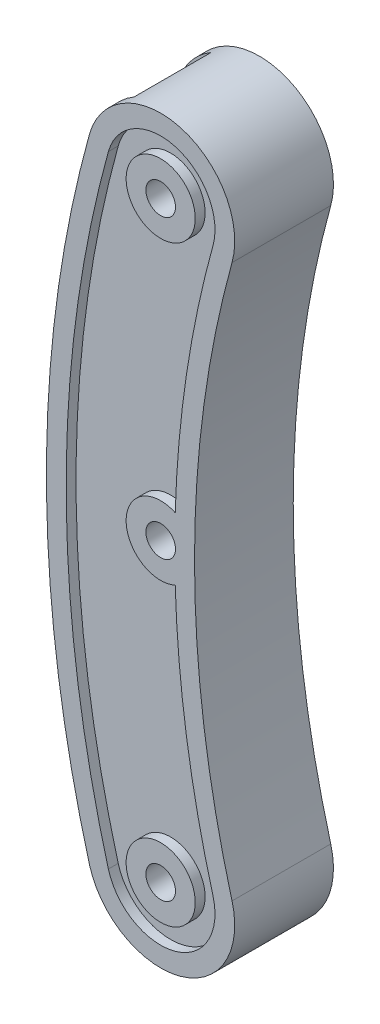
SolidWorks part; units mm, degrees
ref_plane "Front Plane" through (0, 0, 0) normal (0, 0, 1) x (1, 0, 0)
ref_plane "Top Plane" through (0, 0, 0) normal (0, 1, 0) x (1, 0, 0)
ref_plane "Right Plane" through (0, 0, 0) normal (1, 0, 0) x (0, 0, -1)
sketch "Sketch1" plane through (0, 0, 0) normal (0, 0, 1) x (1, 0, 0)
  line L0 (0, 0) -> (-135.8667, 37.5924) construction
  line L2 (-145.3729, 0) -> (0, 0) construction
  line L3 (0, 0) -> (-135.8667, -37.5924) construction
  line L4 (-108.4262, 30) -> (-108.4262, -30) construction
  circle A0 centre (0, 0) radius 105
  circle A1 centre (0, 0) radius 120
  arc A2 (-115.6547, 32) -> (-101.1978, 28) centre (-108.4262, 30) cw
  arc A3 (-115.6547, -32) -> (-101.1978, -28) centre (-108.4262, -30) ccw
  circle A4 centre (-108.4262, -30) radius 1.5
  circle A5 centre (-108.4262, 0) radius 1.5
  circle A6 centre (-108.4262, 30) radius 1.5
  dimension "D1" = 240
  dimension "D2" = 210
  dimension "D4" = 3
  dimension "D3" = 60
extrude "Boss-Extrude1" add sketch "Sketch1" along normal mid plane 10 contours A1 A3 A0 A2 A6 A5 A4
sketch "Sketch2" plane through (0, 0, 5) normal (0, 0, 1) x (1, 0, 0)
  circle A5 centre (-108.4262, -30) radius 3.5
  circle A6 centre (-108.4262, -30) radius 3.5
  arc A10 (-113.7271, 31.4667) -> (-113.7271, -31.4667) centre (0, 0) ccw
  circle A11 centre (-108.4262, 0) radius 3.5
  circle A12 centre (-108.4262, 0) radius 3.5
  circle A14 centre (-108.4262, 30) radius 3.5
  circle A15 centre (-108.4262, 30) radius 3.5
  arc A18 (-113.7271, -31.4667) -> (-103.1254, -28.5333) centre (-108.4262, -30) ccw
  arc A19 (-103.1254, 28.5333) -> (-103.1254, -28.5333) centre (0, 0) ccw
  arc A20 (-103.1254, 28.5333) -> (-113.7271, 31.4667) centre (-108.4262, 30) ccw
  arc A21 (-113.7271, 31.4667) -> (-113.7271, -31.4667) centre (0, 0) ccw
  arc A22 (-113.7271, -31.4667) -> (-103.1254, -28.5333) centre (-108.4262, -30) ccw
  arc A23 (-103.1254, 28.5333) -> (-103.1254, -28.5333) centre (0, 0) ccw
  arc A24 (-103.1254, 28.5333) -> (-113.7271, 31.4667) centre (-108.4262, 30) ccw
  arc A25 (-115.6547, 32) -> (-115.6547, -32) centre (0, 0) ccw
  arc A26 (-115.6547, -32) -> (-101.1978, -28) centre (-108.4262, -30) ccw
  arc A27 (-101.1978, 28) -> (-101.1978, -28) centre (0, 0) ccw
  arc A28 (-101.1978, 28) -> (-115.6547, 32) centre (-108.4262, 30) ccw
  arc A29 (-115.6547, 32) -> (-115.6547, -32) centre (0, 0) ccw
  arc A30 (-115.6547, -32) -> (-101.1978, -28) centre (-108.4262, -30) ccw
  arc A31 (-101.1978, 28) -> (-101.1978, -28) centre (0, 0) ccw
  arc A32 (-101.1978, 28) -> (-115.6547, 32) centre (-108.4262, 30) ccw
  dimension "D1" = 2
  dimension "D2" = 2
  dimension "D3" = 2
  dimension "D4" = 2
  dimension "D5" = 0
extrude "Cut-Extrude1" cut sketch "Sketch2" against normal blind 1 contours A23 A24 A21 A22 A12 A15 A6
sketch "Sketch3" plane through (0, 0, 0) normal (0, 0, 1) x (1, 0, 0)
  line L1 (-109.0825, 45) -> (-139.0825, 45)
  line L2 (-109.0825, 45) -> (-109.0825, -45)
  line L3 (-109.0825, -45) -> (-139.0825, -45)
  line L4 (-139.0825, 45) -> (-139.0825, -45)
  circle A1 centre (0, 0) radius 118
  arc A2 (-113.7271, 31.4667) -> (-113.7271, -31.4667) centre (0, 0) ccw
  arc A3 (-113.7271, 31.4667) -> (-113.7271, -31.4667) centre (0, 0) ccw
  point P5 (-108.7943, -45.6924)
  dimension "D2" = 45
  dimension "D3" = 30
  dimension "D1" = 2
extrude "Cut-Extrude2" cut sketch "Sketch3" against normal mid plane 7.8 contours A1 L1 L4 L3
